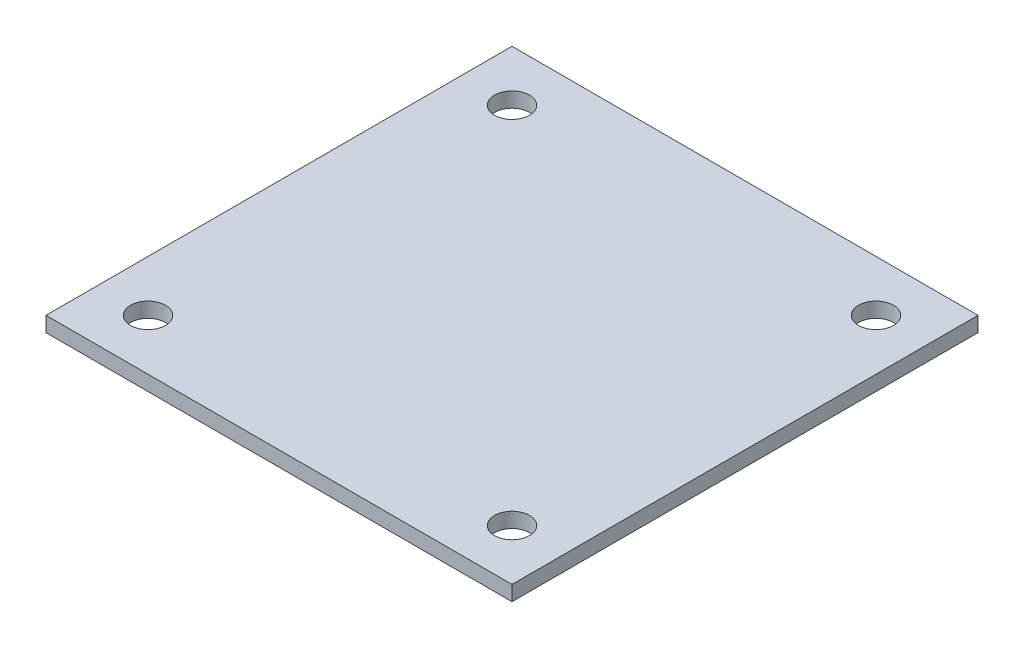
SolidWorks part; units mm, degrees
ref_plane "Front Plane" through (0, 0, 0) normal (0, 0, 1) x (1, 0, 0)
ref_plane "Top Plane" through (0, 0, 0) normal (0, 1, 0) x (1, 0, 0)
ref_plane "Right Plane" through (0, 0, 0) normal (1, 0, 0) x (0, 0, -1)
sketch "Sketch1" plane through (0, 0, 0) normal (0, 1, 0) x (1, 0, 0)
  line L0 (0, -55) -> (0, 55) construction
  line L1 (-23.3, 23.3) -> (23.3, 23.3)
  line L2 (-23.3, 23.3) -> (-23.3, -23.3)
  line L3 (-23.3, -23.3) -> (23.3, -23.3)
  line L4 (23.3, 23.3) -> (23.3, -23.3)
  line L5 (-23.3, 23.3) -> (23.3, -23.3) construction
  line L6 (-23.3, -23.3) -> (23.3, 23.3) construction
  circle A0 centre (-18.2, 18.2) radius 1.75
  circle A1 centre (-18.2, -18.2) radius 1.75
  circle A2 centre (18.2, -18.2) radius 1.75
  circle A3 centre (18.2, 18.2) radius 1.75
  point P0 (0, 0)
  dimension "D2" = 3.5
  dimension "D4" = 5.1
  dimension "D1" = 46.6
  dimension "D3" = 5.1
extrude "Boss-Extrude1" add sketch "Sketch1" along normal blind 1.5
